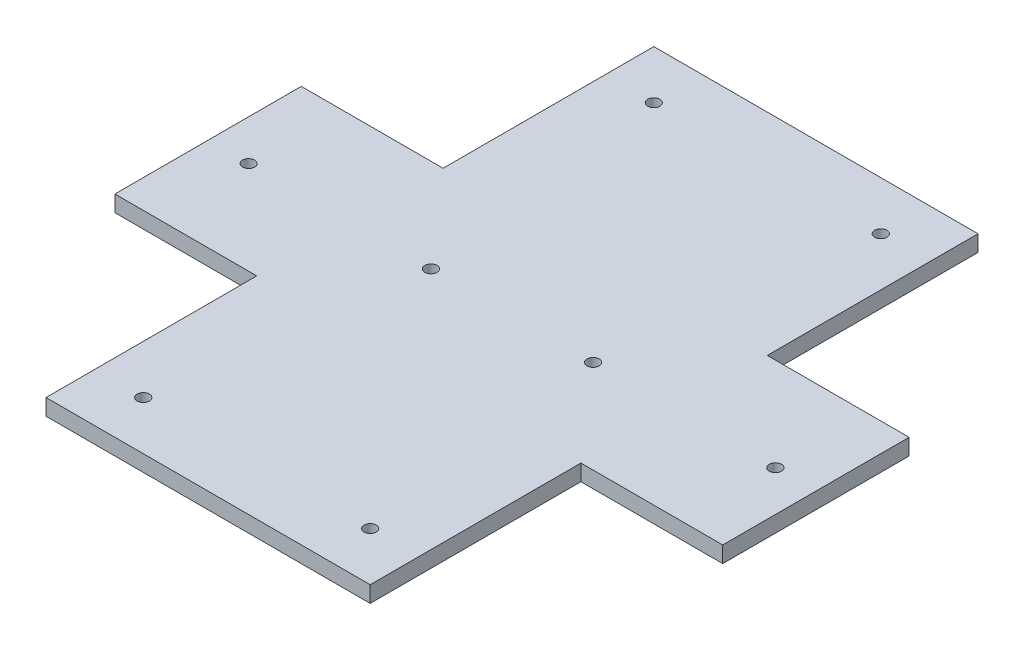
SolidWorks part; units mm, degrees
ref_plane "Front Plane" through (0, 0, 0) normal (0, 0, 1) x (1, 0, 0)
ref_plane "Top Plane" through (0, 0, 0) normal (0, 1, 0) x (1, 0, 0)
ref_plane "Right Plane" through (0, 0, 0) normal (1, 0, 0) x (0, 0, -1)
sketch "Sketch1" plane through (0, 0, 0) normal (0, 1, 0) x (1, 0, 0)
  line L0 (-75, 0) -> (75, 0) construction
  line L1 (-75, -23) -> (-40, -23)
  line L2 (-75, -23) -> (-75, 23)
  line L3 (-75, 23) -> (-40, 23)
  line L4 (75, -23) -> (75, 23)
  line L5 (-75, -23) -> (75, 23) construction
  line L6 (-75, 23) -> (75, -23) construction
  line L7 (0, 23) -> (0, -23) construction
  line L8 (-40, 23) -> (-40, 75)
  line L9 (-40, -75) -> (40, -75)
  line L10 (-40, -75) -> (-40, -23)
  line L11 (-40, 75) -> (40, 75)
  line L12 (40, -75) -> (40, -23)
  line L13 (-40, -75) -> (40, 75) construction
  line L14 (-40, 75) -> (40, -75) construction
  line L15 (40, -23) -> (75, -23)
  line L16 (40, 23) -> (75, 23)
  line L17 (40, 23) -> (40, 75)
  line L18 (-28, 63) -> (-28, -63) construction
  line L19 (-28, -63) -> (28, -63) construction
  line L20 (28, -63) -> (28, 63) construction
  line L21 (28, 63) -> (-28, 63) construction
  circle A0 centre (20, 0) radius 1.5
  circle A1 centre (65, 0) radius 1.5
  circle A2 centre (-65, 0) radius 1.5
  circle A3 centre (-20, 0) radius 1.5
  circle A4 centre (-28, 63) radius 1.5
  circle A5 centre (28, 63) radius 1.5
  circle A6 centre (28, -63) radius 1.5
  circle A7 centre (-28, -63) radius 1.5
  point P0 (0, 0)
  point P20 (0, 0)
  dimension "D7" = 3
  dimension "D8" = 3
  dimension "D9" = 3
  dimension "D10" = 3
  dimension "D1" = 150
  dimension "D2" = 46
  dimension "D3" = 20
  dimension "D4" = 45
  dimension "D5" = 80
  dimension "D6" = 150
  dimension "D11" = 12
  dimension "D12" = 12
  dimension "D13" = 12
  dimension "D14" = 12
extrude "Boss-Extrude1" add sketch "Sketch1" along normal blind 4
